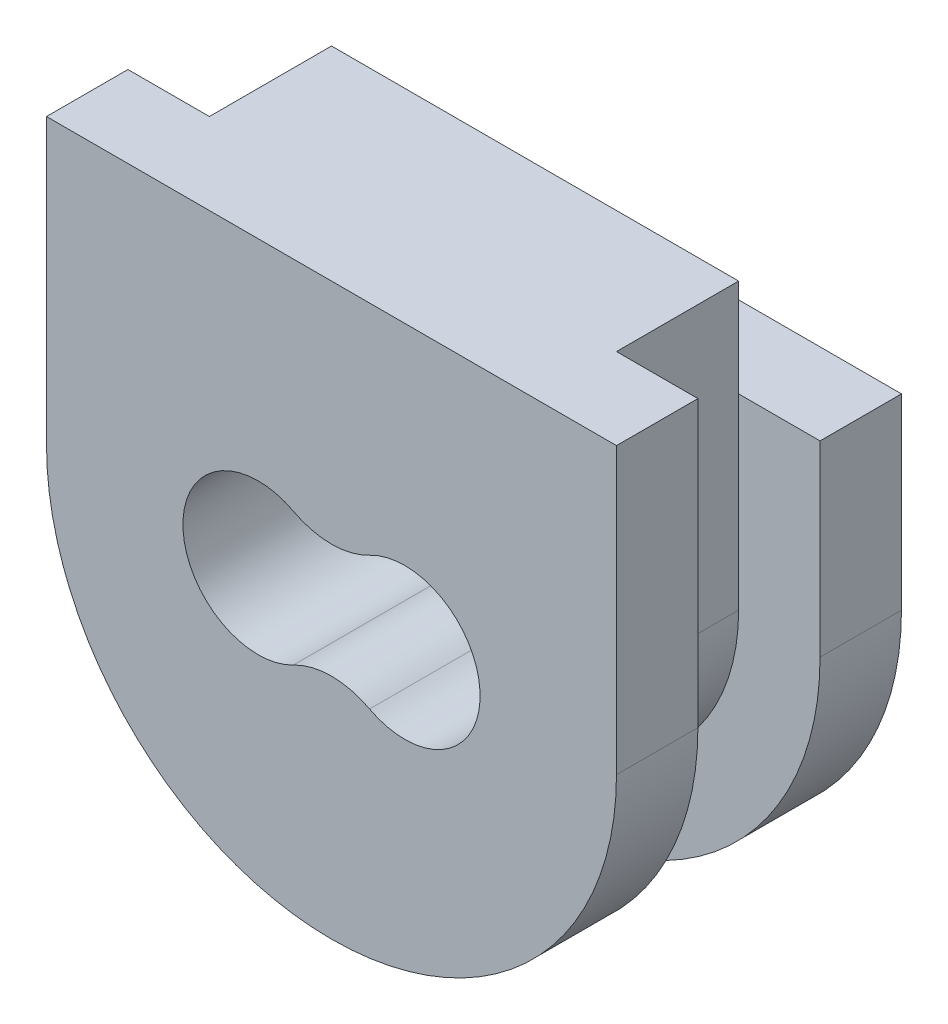
SolidWorks part; units mm, degrees
material "Caoutchouc"
ref_plane "Plan de face" through (0, 0, 0) normal (0, 0, 1) x (1, 0, 0)
ref_plane "Plan de dessus" through (0, 0, 0) normal (0, 1, 0) x (1, 0, 0)
ref_plane "Plan de droite" through (0, 0, 0) normal (1, 0, 0) x (0, 0, -1)
sketch "Esquisse1" plane through (0, 0, 0) normal (0, 0, 1) x (1, 0, 0)
  line L0 (-5, 0) -> (-5, 7)
  line L1 (5, 0) -> (5, 7)
  line L2 (-5, 7) -> (5, 7)
  arc A0 (-5, 0) -> (5, 0) centre (0, 0) ccw
  dimension "D1" = 10
  dimension "D2" = 12
extrude "Boss.-Extru.1" add sketch "Esquisse1" along normal blind 3
sketch "Esquisse2" plane through (0, 0, 0) normal (0, 0, 1) x (1, 0, 0)
  line L3 (-7, 7) -> (7, 7)
  line L4 (5, 7) -> (-5, 7) construction
  line L6 (-7, 9) -> (-7, 0)
  line L7 (7, 9) -> (-7, 9)
  line L8 (7, 0) -> (7, 9)
  line L9 (-7, 7) -> (-7, 0)
  line L11 (7, 0) -> (7, 7)
  arc A2 (-7, 0) -> (7, 0) centre (0, 0) ccw
  arc A3 (-7, 0) -> (7, 0) centre (0, 0) ccw
  dimension "D1" = 2
extrude "Boss.-Extru.2" add sketch "Esquisse2" against normal blind 2
sketch "Esquisse3" plane through (0, 0, 3) normal (0, 0, 1) x (1, 0, 0)
  line L3 (7, 7) -> (-7, 7)
  line L4 (7, 0) -> (7, 7)
  line L5 (-7, 7) -> (-7, 0)
  line L6 (7, 7) -> (-7, 7)
  line L7 (7, 0) -> (7, 7)
  line L8 (-7, 7) -> (-7, 0)
  arc A1 (-7, 0) -> (7, 0) centre (0, 0) ccw
  arc A2 (-7, 0) -> (7, 0) centre (0, 0) ccw
  dimension "D1" = 0
extrude "Boss.-Extru.3" add sketch "Esquisse3" along normal blind 2
sketch "Esquisse4" plane through (0, 0, 0) normal (0, 0, 1) x (1, 0, 0)
  line L0 (0, 0) -> (0, -1.9549) construction
  line L1 (1.8, 0) -> (-1.8, 0) construction
  arc A0 (0.9351, -1.6354) -> (0.9351, 1.6354) centre (1.8, 0) ccw
  arc A1 (-0.9351, 1.6354) -> (-0.9351, -1.6354) centre (-1.8, 0) ccw
  arc A2 (-0.9351, -1.6354) -> (0.9351, -1.6354) centre (0, -3.4033) cw
  arc A3 (0.9351, 1.6354) -> (-0.9351, 1.6354) centre (0, 3.4033) cw
  point P9 (0, -0.4272)
  dimension "D1" = 3.7
  dimension "D3" = 2
  dimension "D2" = 3.6
extrude "Enlèv. mat.-Extru.1" cut sketch "Esquisse4" against normal through all and the other way through all
sketch "Esquisse5" plane through (0, 0, -2) normal (0, 0, -1) x (-1, 0, 0)
  line L0 (7, 7) -> (7, 0) construction
  line L1 (-7, 7) -> (7, 7)
  line L2 (-7, 7) -> (-7, 4.6)
  line L3 (-7, 4.6) -> (7, 4.6)
  line L4 (7, 7) -> (7, 4.6)
  dimension "D1" = 2.4
extrude "Enlèv. mat.-Extru.2" cut sketch "Esquisse5" against normal up to surface (2 mm away) up to face at (0.25, 2, 0)
